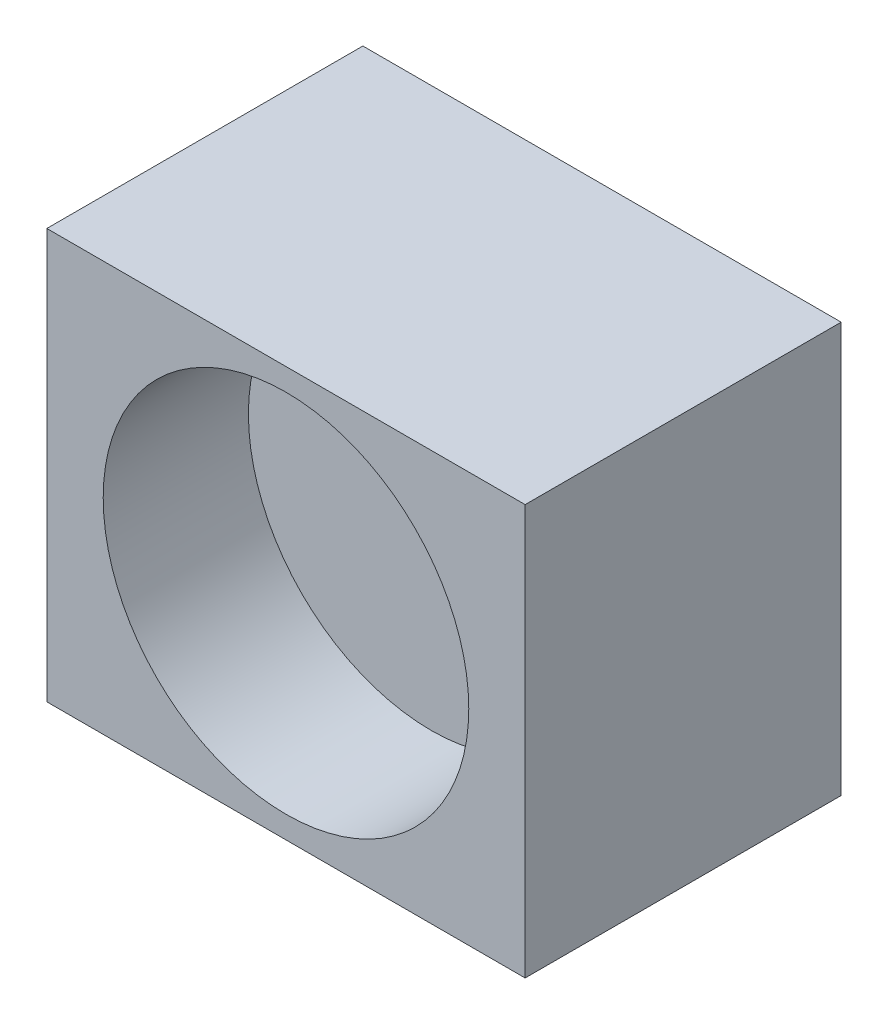
SolidWorks part; units mm, degrees
ref_plane "Front Plane" through (0, 0, 0) normal (0, 0, 1) x (1, 0, 0)
ref_plane "Top Plane" through (0, 0, 0) normal (0, 1, 0) x (1, 0, 0)
ref_plane "Right Plane" through (0, 0, 0) normal (1, 0, 0) x (0, 0, -1)
sketch "Sketch1" plane through (0, 0, 0) normal (0, 0, 1) x (1, 0, 0)
  line L1 (-28, 24) -> (28, 24)
  line L2 (-28, 24) -> (-28, -24)
  line L3 (-28, -24) -> (28, -24)
  line L4 (28, 24) -> (28, -24)
  line L5 (-28, 24) -> (28, -24) construction
  line L6 (-28, -24) -> (28, 24) construction
  point P0 (0, 0)
  dimension "D1" = 48
  dimension "D2" = 56
extrude "Boss-Extrude1" add sketch "Sketch1" along normal blind 37
sketch "Sketch2" plane through (0, 0, 37) normal (0, 0, 1) x (1, 0, 0)
  circle A0 centre (0, 0) radius 21.4
  dimension "D1" = 42.8
extrude "Cut-Extrude1" cut sketch "Sketch2" against normal blind 17
sketch "Sketch4" plane through (0, -24, 0) normal (0, -1, 0) x (1, 0, 0)
  line L0 (0, 0) -> (23, 0)
  line L1 (-28, 0) -> (28, 0) construction
  line L5 (-24, 33.5) -> (24, 33.5) construction
  line L6 (-24, 33.5) -> (-24, 3.5) construction
  line L7 (-24, 3.5) -> (24, 3.5)
  line L8 (24, 33.5) -> (24, 3.5)
  line L9 (-24, 33.5) -> (24, 3.5) construction
  line L10 (-24, 3.5) -> (24, 33.5) construction
  circle A0 centre (-24, 33.5) radius 2.5
  circle A1 centre (24, 33.5) radius 2.5
  circle A2 centre (24, 3.5) radius 2.5
  circle A3 centre (-24, 3.5) radius 2.5
  point P13 (0, 18.5)
  dimension "D2" = 30
  dimension "D4" = 5
  dimension "D5" = 5
  dimension "D6" = 5
  dimension "D7" = 5
  dimension "D1" = 23
  dimension "D3" = 48
extrude "Cut-Extrude2" cut sketch "Sketch4" against normal blind 5 contours A0 | A3 | A2 | A1
